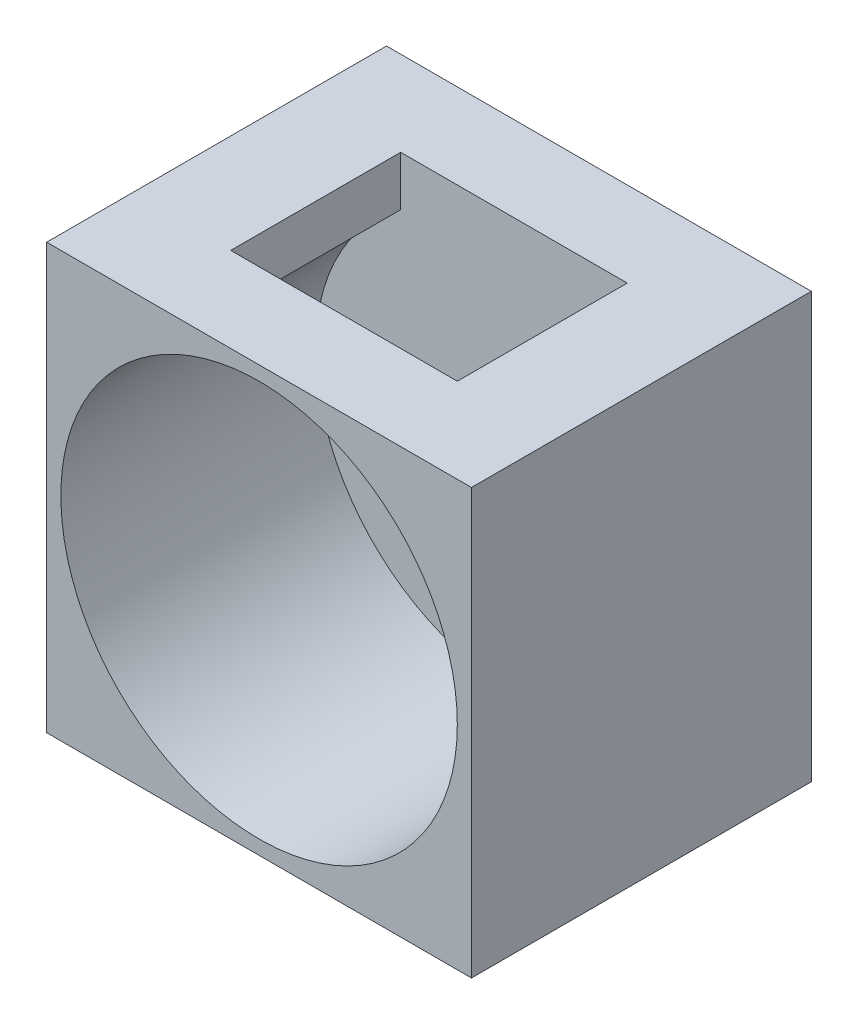
SolidWorks part; units mm, degrees
ref_plane "Alzado" through (0, 0, 0) normal (0, 0, 1) x (1, 0, 0)
ref_plane "Planta" through (0, 0, 0) normal (0, 1, 0) x (1, 0, 0)
ref_plane "Vista lateral" through (0, 0, 0) normal (1, 0, 0) x (0, 0, -1)
sketch "Croquis1" plane through (0, 0, 0) normal (0, 0, 1) x (1, 0, 0)
  line L1 (-7.5, -7.5) -> (7.5, -7.5)
  line L2 (-7.5, -7.5) -> (-7.5, 7.5)
  line L3 (-7.5, 7.5) -> (7.5, 7.5)
  line L4 (7.5, -7.5) -> (7.5, 7.5)
  line L5 (-7.5, -7.5) -> (7.5, 7.5) construction
  line L6 (-7.5, 7.5) -> (7.5, -7.5) construction
  point P0 (0, 0)
extrude "Saliente-Extruir1" add sketch "Croquis1" along normal blind 12
sketch "Croquis2" plane through (0, 7.5, 0) normal (0, 1, 0) x (1, 0, 0)
  line L0 (7.5, 0) -> (-7.5, 0) construction
  line L1 (4, -3) -> (-4, -3)
  line L2 (4, -3) -> (4, -9)
  line L3 (4, -9) -> (-4, -9)
  line L4 (-4, -3) -> (-4, -9)
  line L5 (7.5, -12) -> (-7.5, -12) construction
  line L6 (7.5, -12) -> (7.5, 0) construction
  line L7 (-7.5, -12) -> (-7.5, 0) construction
  point P8 (7.5, -6)
  dimension "D1" = 3
  dimension "D2" = 3
  dimension "D3" = 3.5
  dimension "D4" = 3.5
extrude "Cortar-Extruir1" cut sketch "Croquis2" against normal blind 10
sketch "Croquis3" plane through (0, 0, 12) normal (0, 0, 1) x (1, 0, 0)
  circle A0 centre (0, 0) radius 7
extrude "Cortar-Extruir2" cut sketch "Croquis3" against normal blind 9
